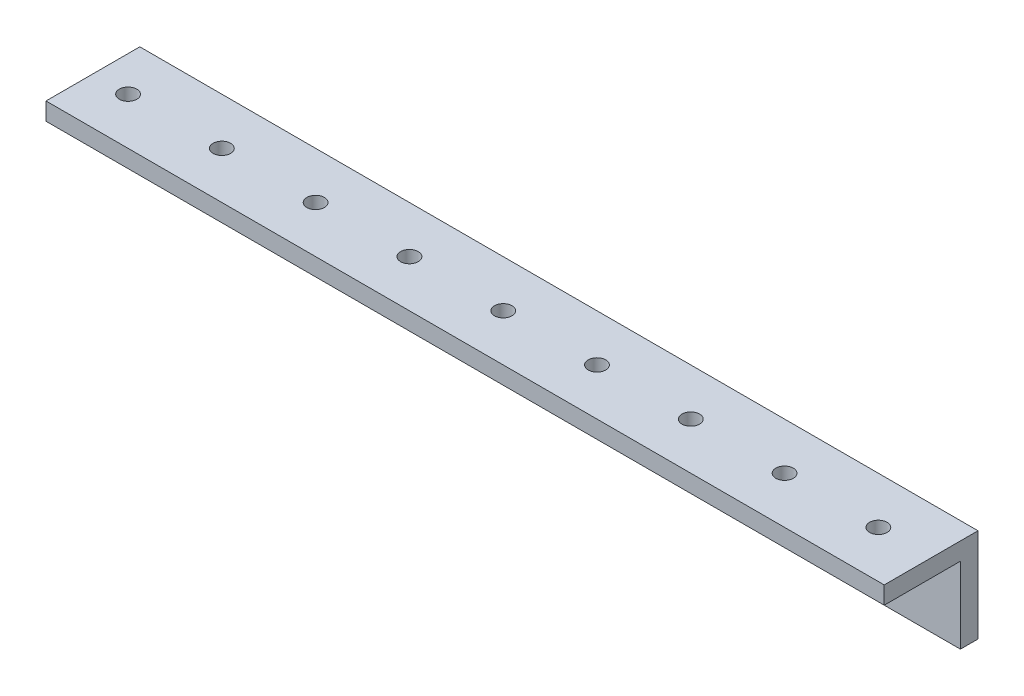
SolidWorks part; units mm, degrees
ref_plane "Front Plane" through (0, 0, 0) normal (0, 0, 1) x (1, 0, 0)
ref_plane "Top Plane" through (0, 0, 0) normal (0, 1, 0) x (1, 0, 0)
ref_plane "Right Plane" through (0, 0, 0) normal (1, 0, 0) x (0, 0, -1)
sketch "Esquisse1" plane through (0, 0, 0) normal (0, 0, 1) x (1, 0, 0)
  line L1 (0, 0) -> (143, 0)
  line L2 (0, 0) -> (0, 16)
  line L3 (0, 16) -> (143, 16)
  line L4 (143, 0) -> (143, 16)
  dimension "D1" = 16
  dimension "D2" = 143
extrude "Boss.-Extru.1" add sketch "Esquisse1" along normal blind 3
ref_plane "Plan1" through (0, 0, 3) normal (0, 0, 1) x (1, 0, 0)
sketch "Esquisse2" plane through (0, 0, 3) normal (0, 0, 1) x (1, 0, 0)
  line L0 (143, 0) -> (143, 16) construction
  line L1 (0, 16) -> (143, 16)
  line L2 (0, 16) -> (0, 13)
  line L3 (0, 13) -> (143, 13)
  line L4 (143, 16) -> (143, 13)
  dimension "D1" = 3
extrude "Boss.-Extru.2" add sketch "Esquisse2" along normal blind 13
ref_plane "Plan2" through (0, 0, 0) normal (0, 0, -1) x (-1, 0, 0)
sketch "Esquisse4" plane through (0, 0, 0) normal (0, 0, -1) x (-1, 0, 0)
  line L0 (0, 0) -> (-143, 0) construction
  line L2 (-143, 0) -> (-143, 16) construction
  circle A0 centre (-134, 8) radius 1.5
  dimension "D1" = 3
  dimension "D2" = 8
  dimension "D3" = 9
extrude "Enlèv. mat.-Extru.1" cut sketch "Esquisse4" against normal blind 10
pattern_linear "Répétition linéaire1" count 9 spacing 16 along (-1, 0, 0) of "Enlèv. mat.-Extru.1"
ref_plane "Plan3" through (0, 16, 0) normal (0, 1, 0) x (1, 0, 0)
sketch "Esquisse5" plane through (0, 16, 0) normal (0, 1, 0) x (1, 0, 0)
  line L0 (143, -16) -> (143, 0) construction
  line L1 (143, -16) -> (0, -16) construction
  circle A0 centre (134, -8) radius 1.5
  dimension "D1" = 3
  dimension "D3" = 8
  dimension "D2" = 9
extrude "Enlèv. mat.-Extru.2" cut sketch "Esquisse5" against normal blind 10
pattern_linear "Répétition linéaire2" count 9 spacing 16 along (-1, 0, 0) of "Enlèv. mat.-Extru.2"
